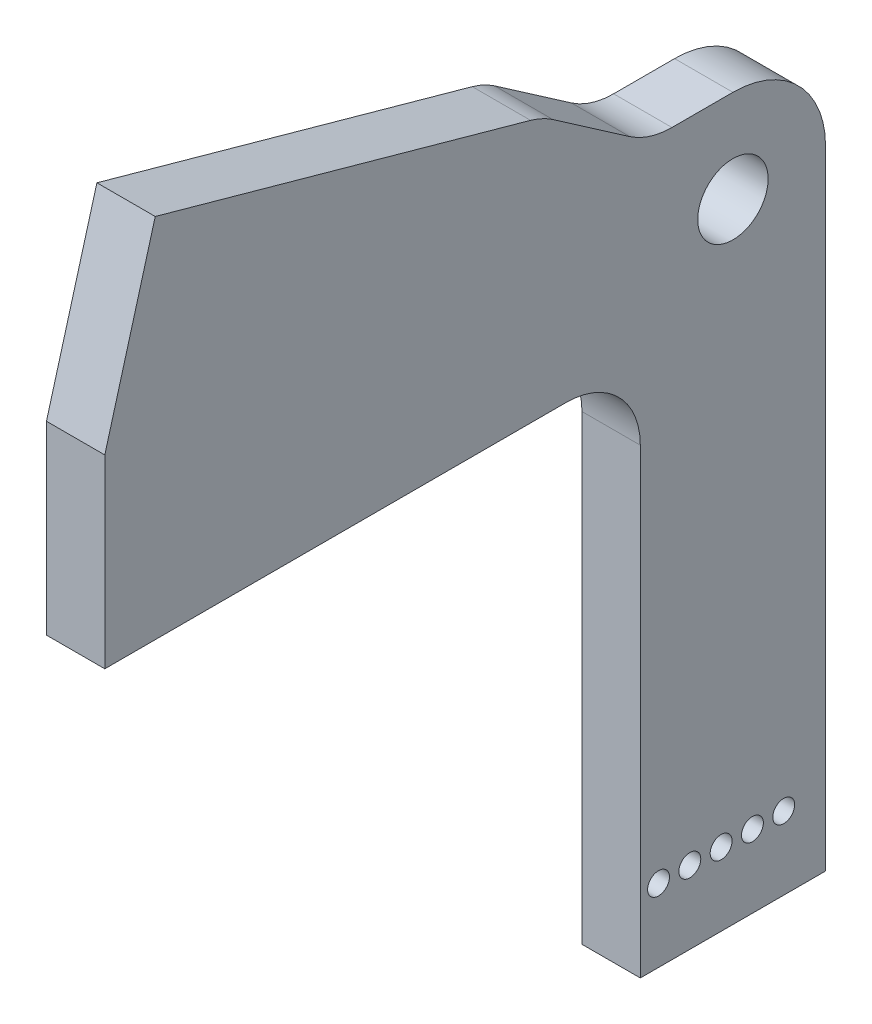
SolidWorks part; units mm, degrees
material "Hardboard"
ref_plane "Front Plane" through (0, 0, 0) normal (0, 0, 1) x (1, 0, 0)
ref_plane "Top Plane" through (0, 0, 0) normal (0, 1, 0) x (1, 0, 0)
ref_plane "Right Plane" through (0, 0, 0) normal (1, 0, 0) x (0, 0, -1)
sketch "Sketch1" plane through (0, 0, 0) normal (1, 0, 0) x (0, 0, -1)
  line L0 (-4.1807, 6.35) -> (0, 6.35)
  line L1 (6.35, 6.35) -> (6.35, 0) construction
  line L2 (6.35, -43.0661) -> (-6.35, -43.0661)
  line L3 (-6.35, -43.0661) -> (-6.35, -11.43)
  line L4 (-11.43, -6.35) -> (-43.0661, -6.35)
  line L5 (-43.0661, -6.35) -> (-43.0661, 6.35)
  line L6 (-6.35, -6.35) -> (6.35, 6.35) construction
  line L7 (-43.0661, 6.35) -> (-39.6083, 18.7801)
  line L8 (-39.6083, 18.7801) -> (-13.872, 11.6206)
  line L9 (-12.3409, 10.9026) -> (-7.0732, 7.2539)
  line L10 (0, 6.35) -> (6.35, 6.35) construction
  line L11 (6.35, 0) -> (6.35, -43.0661)
  circle A0 centre (0, 0) radius 2.413
  circle A1 centre (-5.1, -38.0661) radius 0.75
  circle A2 centre (-2.9545, -38.0661) radius 0.75
  circle A3 centre (-0.8091, -38.0661) radius 0.75
  circle A4 centre (1.3364, -38.0661) radius 0.75
  circle A5 centre (3.4818, -38.0661) radius 0.75
  arc A6 (0, 6.35) -> (6.35, 0) centre (0, 0) cw
  arc A7 (-6.35, -11.43) -> (-11.43, -6.35) centre (-11.43, -11.43) ccw
  arc A8 (-4.1807, 6.35) -> (-7.0732, 7.2539) centre (-4.1807, 11.43) cw
  arc A9 (-12.3409, 10.9026) -> (-13.872, 11.6206) centre (-15.2335, 6.7265) ccw
  point P31 (5.3198, 6.238)
  dimension "D1" = 4.826
  dimension "D2" = 1.5
  dimension "D3" = 1.25
  dimension "D6" = 5.08
  dimension "D7" = 5.08
  dimension "D8" = 5.08
  dimension "D4" = 5
  dimension "D5" = 5
extrude "Boss-Extrude1" add sketch "Sketch1" along normal mid plane 4 contours L9 L8 L7 L0 | L4 L6 A0 L0 L5 | L6 L3 L2 L1 A0 A5 A4 A3 A2 A1
